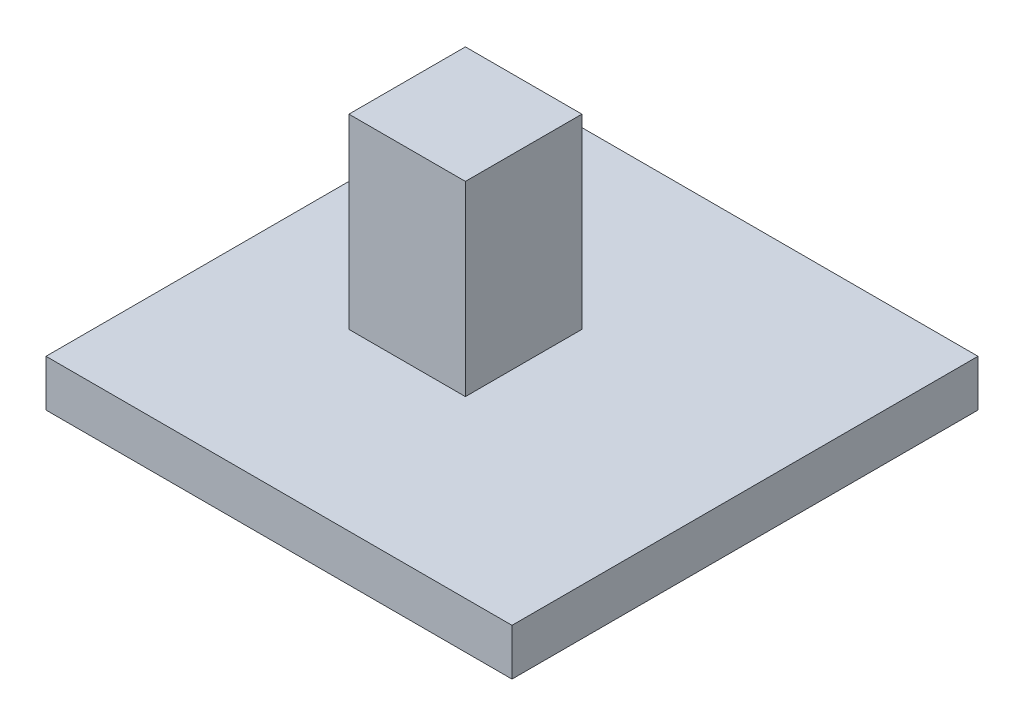
SolidWorks part; units mm, degrees
ref_plane "前视基准面" through (0, 0, 0) normal (0, 0, 1) x (1, 0, 0)
ref_plane "上视基准面" through (0, 0, 0) normal (0, 1, 0) x (1, 0, 0)
ref_plane "右视基准面" through (0, 0, 0) normal (1, 0, 0) x (0, 0, -1)
other "Configuration Table"
sketch "草图1" plane through (0, 0, 0) normal (0, 1, 0) x (1, 0, 0)
  line L1 (-100, 100) -> (100, 100)
  line L2 (-100, 100) -> (-100, -100)
  line L3 (-100, -100) -> (100, -100)
  line L4 (100, 100) -> (100, -100)
  line L5 (-100, 100) -> (100, -100) construction
  line L6 (-100, -100) -> (100, 100) construction
  point P0 (0, 0)
  dimension "D1" = 200
  dimension "D2" = 200
extrude "凸台-拉伸1" add sketch "草图1" along normal blind 20
sketch "草图2" plane through (0, 20, 0) normal (0, 1, 0) x (1, 0, 0)
  line L0 (20, -40) -> (-60, 40) construction
  line L1 (-45, -25) -> (5, -25)
  line L2 (-45, -25) -> (-45, 25)
  line L3 (-45, 25) -> (5, 25)
  line L4 (5, -25) -> (5, 25)
  line L5 (-45, -25) -> (5, 25) construction
  line L6 (-45, 25) -> (5, -25) construction
  point P0 (-20, 0)
  dimension "D1" = 50
  dimension "D2" = 50
extrude "凸台-拉伸2" add sketch "草图2" along normal up to surface (80 mm away)
